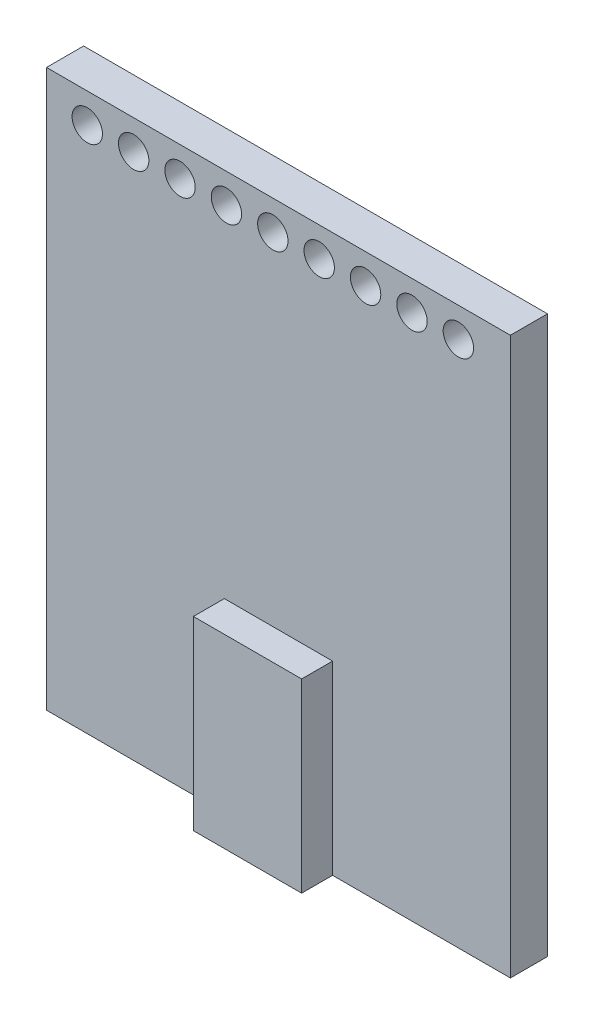
SolidWorks part; units mm, degrees
ref_plane "Front Plane" through (0, 0, 0) normal (0, 0, 1) x (1, 0, 0)
ref_plane "Top Plane" through (0, 0, 0) normal (0, 1, 0) x (1, 0, 0)
ref_plane "Right Plane" through (0, 0, 0) normal (1, 0, 0) x (0, 0, -1)
sketch "Sketch1" plane through (0, 0, 0) normal (0, 0, 1) x (1, 0, 0)
  line L1 (-7.5, 9) -> (7.5, 9)
  line L2 (-7.5, 9) -> (-7.5, -9)
  line L3 (-7.5, -9) -> (7.5, -9)
  line L4 (7.5, 9) -> (7.5, -9)
  line L5 (-7.5, 9) -> (7.5, -9) construction
  line L6 (-7.5, -9) -> (7.5, 9) construction
  point P0 (0, 0)
  dimension "D1" = 15
  dimension "D2" = 18
extrude "Boss-Extrude1" add sketch "Sketch1" along normal blind 1.2
sketch "Sketch2" plane through (0, 0, 1.2) normal (0, 0, 1) x (1, 0, 0)
  line L0 (-7.5, -9) -> (7.5, -9) construction
  line L1 (-1.75, -9) -> (1.75, -9)
  line L2 (-1.75, -9) -> (-1.75, -3)
  line L3 (-1.75, -3) -> (1.75, -3)
  line L4 (1.75, -9) -> (1.75, -3)
  point P6 (0, -9)
  dimension "D1" = 6
  dimension "D2" = 3.5
extrude "Boss-Extrude2" add sketch "Sketch2" along normal blind 1
sketch "Sketch3" plane through (0, 0, 1.2) normal (0, 0, 1) x (1, 0, 0)
  circle A0 centre (-6.1819, 8.0414) radius 0.4915
  circle A1 centre (-4.6819, 8.0414) radius 0.4915
  circle A2 centre (-3.1819, 8.0414) radius 0.4915
  circle A3 centre (-1.6819, 8.0414) radius 0.4915
  circle A4 centre (-0.1819, 8.0414) radius 0.4915
  circle A5 centre (1.3181, 8.0414) radius 0.4915
  circle A6 centre (2.8181, 8.0414) radius 0.4915
  circle A7 centre (4.3181, 8.0414) radius 0.4915
  circle A8 centre (5.8181, 8.0414) radius 0.4915
  dimension "D1" = 9
extrude "Cut-Extrude1" cut sketch "Sketch3" against normal blind 1
